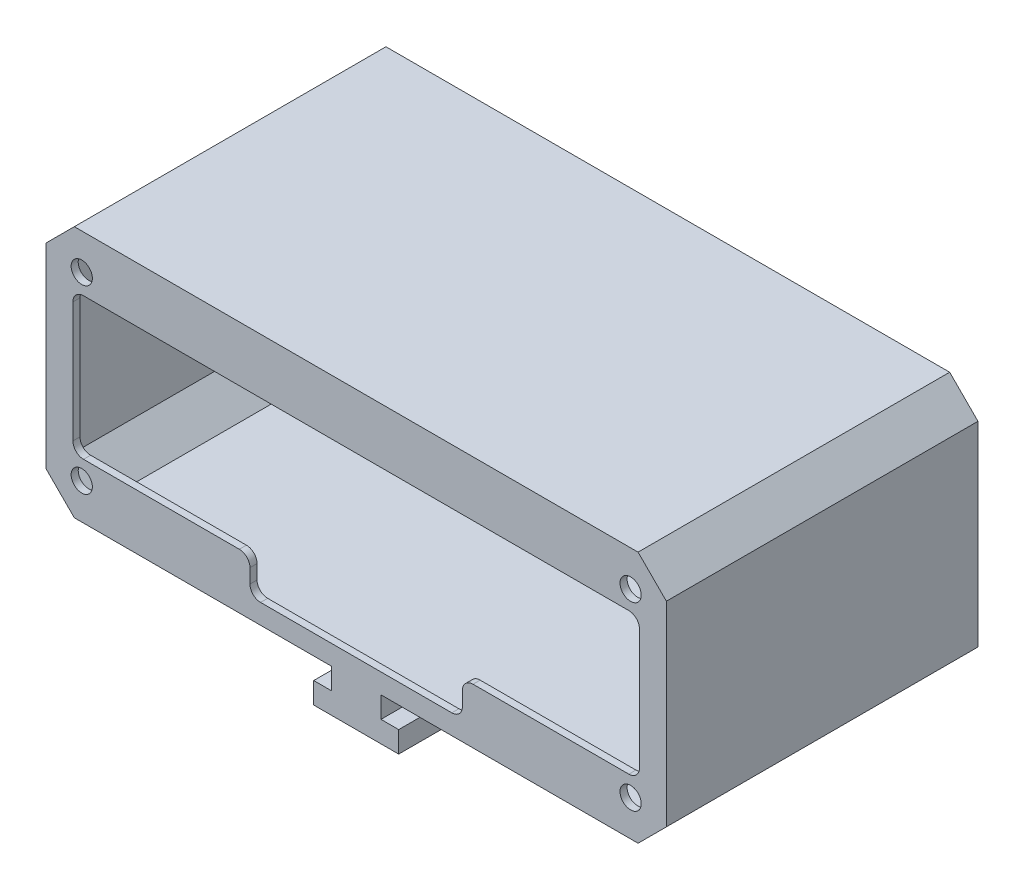
SolidWorks part; units mm, degrees
ref_plane "前基準面" through (0, 0, 0) normal (0, 0, 1) x (1, 0, 0)
ref_plane "上基準面" through (0, 0, 0) normal (0, 1, 0) x (1, 0, 0)
ref_plane "右基準面" through (0, 0, 0) normal (1, 0, 0) x (0, 0, -1)
sketch "草圖1" plane through (0, 0, 0) normal (0, 0, 1) x (1, 0, 0)
  line L0 (-43.8, 17.8) -> (43.8, 17.8)
  line L1 (-43, 17) -> (43, 17)
  line L2 (-43, 17) -> (-43, -17)
  line L3 (-43, -17) -> (43, -17)
  line L4 (43, 17) -> (43, -17)
  line L5 (43.8, 17.8) -> (43.8, -17.8)
  line L6 (-43.8, -17.8) -> (43.8, -17.8)
  line L7 (-43.8, 17.8) -> (-43.8, -17.8)
  point P4 (0, 17)
  point P6 (-43, 0)
  dimension "D1" = 86
  dimension "D2" = 34
  dimension "D3" = 0.8
extrude "填料-伸長1" add sketch "草圖1" along normal blind 43
chamfer "導角1" distance 4 angle 45 8 edges at (43, 17, 21.5) (43.8, 17.8, 21.5) (43, -17, 21.5) (43.8, -17.8, 21.5) (-43, -17, 21.5) (-43.8, -17.8, 21.5) (-43, 17, 21.5) (-43.8, 17.8, 21.5)
sketch "草圖2" plane through (0, 0, 43) normal (0, 0, 1) x (1, 0, 0)
  line L0 (-43.8, 13.8) -> (-39.8, 17.8)
  line L1 (-39.8, 17.8) -> (39.8, 17.8)
  line L2 (39.8, 17.8) -> (43.8, 13.8)
  line L3 (43.8, 13.8) -> (43.8, -13.8)
  line L4 (43.8, -13.8) -> (39.8, -17.8)
  line L5 (39.8, -17.8) -> (-39.8, -17.8)
  line L6 (-39.8, -17.8) -> (-43.8, -13.8)
  line L7 (-43.8, -13.8) -> (-43.8, 13.8)
extrude "填料-伸長2" add sketch "草圖2" along normal blind 1
sketch "草圖3" plane through (0, 0, 44) normal (0, 0, 1) x (1, 0, 0)
  line L0 (15, -10) -> (40, -10)
  line L1 (-40, 10) -> (40, 10)
  line L2 (-40, 10) -> (-40, -10)
  line L3 (-40, -10) -> (-15, -10)
  line L4 (40, 10) -> (40, -10)
  line L6 (-15, -10) -> (-15, -15)
  line L7 (-15, -15) -> (15, -15)
  line L8 (15, -10) -> (15, -15)
  point P4 (0, 10)
  point P6 (-40, 0)
  point P11 (0, -15)
  dimension "D1" = 20
  dimension "D2" = 80
  dimension "D3" = 30
  dimension "D4" = 5
extrude "除料-伸長1" cut sketch "草圖3" against normal through all
fillet "圓角1" radius 1.5 8 edges at (40, 10, 43.5) (40, -10, 43.5) (15, -10, 43.5) (15, -15, 43.5) (-15, -15, 43.5) (-15, -10, 43.5) (-40, -10, 43.5) (-40, 10, 43.5)
sketch "草圖4" plane through (0, 0, 43) normal (0, 0, -1) x (-1, 0, 0)
  line L0 (0, 17) -> (0, -17) construction
  line L1 (-39, 17) -> (39, 17) construction
  line L2 (39, -17) -> (-39, -17) construction
  line L3 (-43, 0) -> (43, 0) construction
  line L4 (-43, -13) -> (-43, 13) construction
  line L5 (43, 13) -> (43, -13) construction
  circle A0 centre (-38.75, 12.75) radius 1.5
  circle A1 centre (38.75, 12.75) radius 1.5
  circle A2 centre (38.75, -12.75) radius 1.5
  circle A3 centre (-38.75, -12.75) radius 1.5
  dimension "D3" = 3
  dimension "D1" = 4.25
  dimension "D2" = 4.25
extrude "除料-伸長2" cut sketch "草圖4" against normal through all
sketch "草圖5" plane through (0, -17.8, 0) normal (0, -1, 0) x (1, 0, 0)
  line L0 (-39.8, 0) -> (39.8, 0) construction
  line L1 (6, 0) -> (-6, 0)
  line L2 (6, 0) -> (6, 44)
  line L3 (6, 44) -> (-6, 44)
  line L4 (-6, 0) -> (-6, 44)
  line L5 (-39.8, 44) -> (39.8, 44) construction
  dimension "D1" = 6
  dimension "D2" = 12
extrude "填料-伸長3" add sketch "草圖5" along normal blind 6
sketch "草圖6" plane through (0, 0, 44) normal (0, 0, 1) x (1, 0, 0)
  line L0 (6, -23.8) -> (6, -17.8) construction
  line L1 (6, -20.8) -> (3.5, -20.8)
  line L2 (6, -20.8) -> (6, -17.8)
  line L3 (6, -17.8) -> (3.5, -17.8)
  line L4 (3.5, -20.8) -> (3.5, -17.8)
  line L5 (-6, -23.8) -> (-6, -17.8) construction
  line L6 (-6, -20.8) -> (-3.5, -20.8)
  line L7 (-6, -20.8) -> (-6, -17.8)
  line L8 (-6, -17.8) -> (-3.5, -17.8)
  line L9 (-3.5, -20.8) -> (-3.5, -17.8)
  dimension "D1" = 2.5
  dimension "D2" = 2.5
  dimension "D3" = 3
  dimension "D4" = 3
extrude "除料-伸長3" cut sketch "草圖6" against normal through all
sketch "草圖7" plane through (0, -23.8, 0) normal (0, -1, 0) x (1, 0, 0)
  line L0 (-6, 0) -> (6, 0) construction
  circle A0 centre (0, 6) radius 4
  circle A1 centre (0, 21) radius 4
  circle A2 centre (0, 36) radius 4
  dimension "D1" = 8
  dimension "D2" = 6
  dimension "D3" = 3
extrude "除料-伸長4" cut sketch "草圖7" against normal blind 2.2
